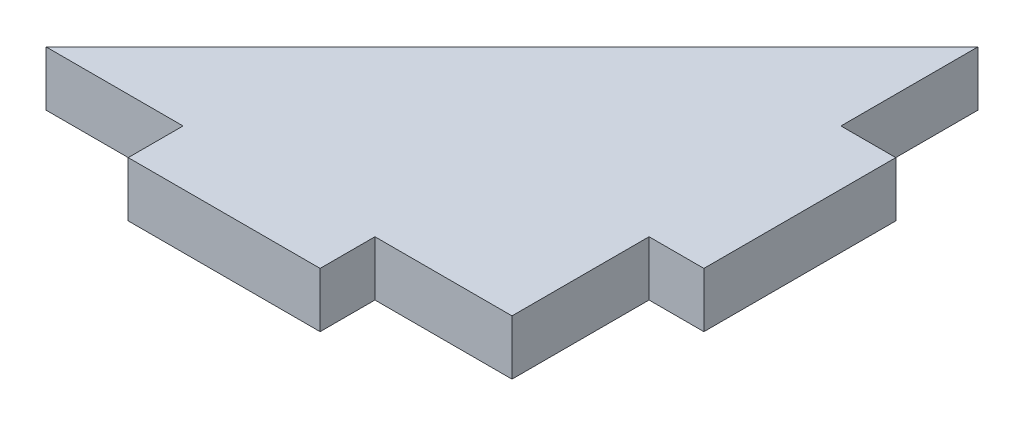
SolidWorks part; units mm, degrees
ref_plane "Front Plane" through (0, 0, 0) normal (0, 0, 1) x (1, 0, 0)
ref_plane "Top Plane" through (0, 0, 0) normal (0, 1, 0) x (1, 0, 0)
ref_plane "Right Plane" through (0, 0, 0) normal (1, 0, 0) x (0, 0, -1)
sketch "Sketch1" plane through (0, 0, 0) normal (0, 1, 0) x (1, 0, 0)
  line L0 (0, 0) -> (-17, 0)
  line L1 (-17, 0) -> (0, 17)
  line L2 (0, 17) -> (0, 0)
  line L4 (-12, 0) -> (-5, 0)
  line L5 (-12, 0) -> (-12, -2)
  line L6 (-12, -2) -> (-5, -2)
  line L7 (-5, 0) -> (-5, -2)
  line L8 (0, 5) -> (2, 5)
  line L9 (0, 5) -> (0, 12)
  line L10 (0, 12) -> (2, 12)
  line L11 (2, 5) -> (2, 12)
  dimension "D1" = 90
  dimension "D2" = 17
  dimension "D3" = 17
  dimension "D4" = 24.0416
  dimension "D5" = 2
  dimension "D6" = 2
  dimension "D7" = 7
  dimension "D8" = 7
  dimension "D9" = 5
  dimension "D10" = 5
  dimension "D11" = 5
  dimension "D12" = 5
extrude "Boss-Extrude1" add sketch "Sketch1" along normal blind 2 contours L2 L1 L0 | L7 L0 L5 L6 | L8 L11 L10 L2
